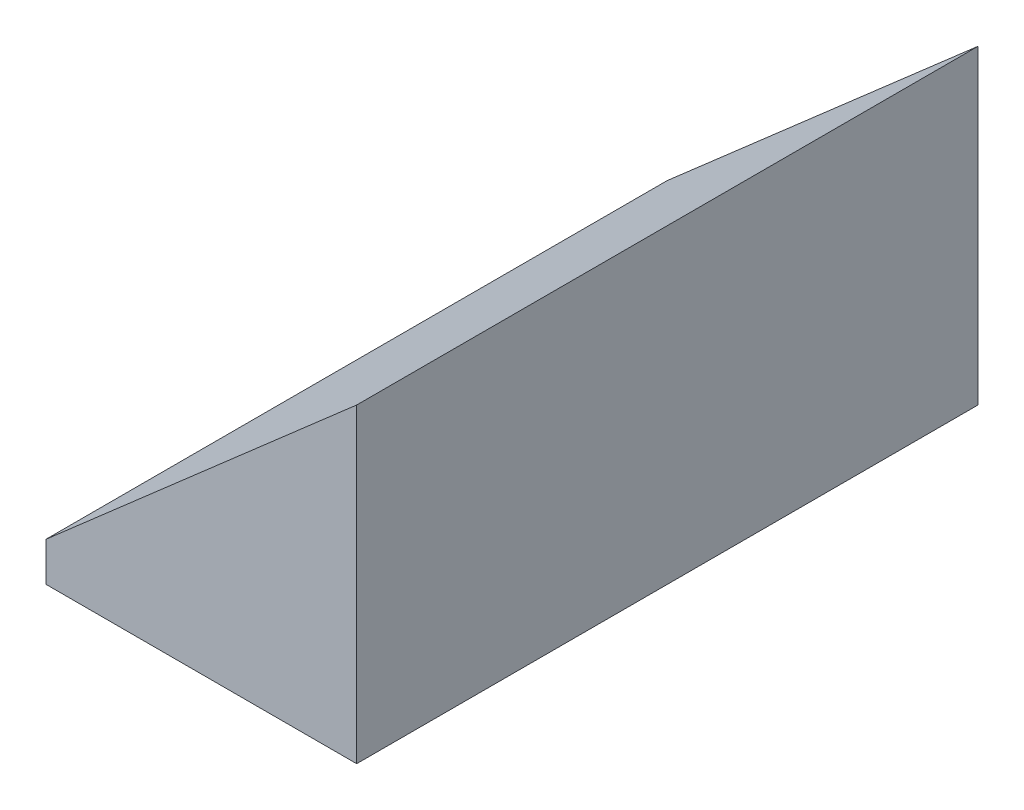
SolidWorks part; units mm, degrees
ref_plane "Front Plane" through (0, 0, 0) normal (0, 0, 1) x (1, 0, 0)
ref_plane "Top Plane" through (0, 0, 0) normal (0, 1, 0) x (1, 0, 0)
ref_plane "Right Plane" through (0, 0, 0) normal (1, 0, 0) x (0, 0, -1)
sketch "Sketch1" plane through (0, 0, 0) normal (0, 0, 1) x (1, 0, 0)
  line L0 (0, 0) -> (0, 7.95)
  line L2 (-7.95, 0) -> (0, 0)
  line L3 (-7.95, 0) -> (-7.95, 1)
  line L4 (-7.95, 1) -> (0, 7.95)
  dimension "D1" = 7.95
  dimension "D2" = 7.95
  dimension "D3" = 1
extrude "Boss-Extrude1" add sketch "Sketch1" against normal blind 15.9
shell "Shell1" thickness 0.3
sketch "Sketch2" plane through (0, 0, 0) normal (0, 1, 0) x (1, 0, 0)
  line L0 (-7.65, 15.6) -> (-0.3, 0.3) construction
  line L1 (-0.3, 0.3) -> (-7.65, 0.3) construction
  line L2 (-7.65, 0.3) -> (-0.3, 15.6) construction
  circle A0 centre (-3.975, 7.95) radius 1.5
  circle A1 centre (-3.975, 7.95) radius 0.5
  point P11 (0, 0)
  point P13 (0, 0)
  dimension "D1" = 3
  dimension "D2" = 1
extrude "Boss-Extrude2" add sketch "Sketch2" along normal up to surface (4.0765 mm away) up to face at (-3.975, 4.0765, -7.95)
